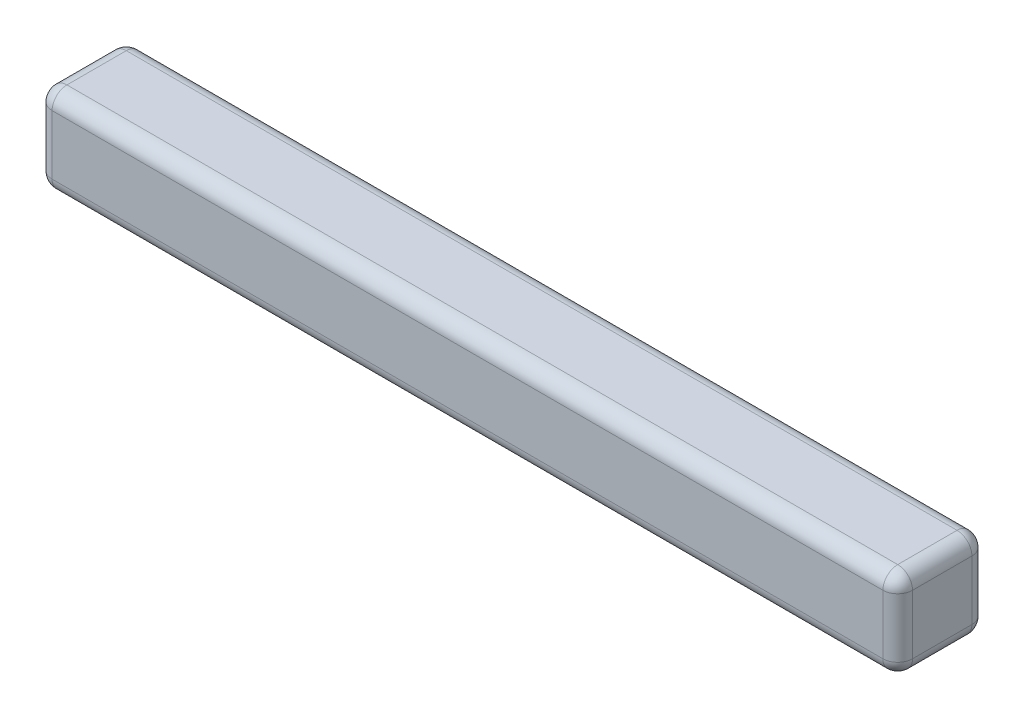
SolidWorks part; units mm, degrees
ref_plane "Front Plane" through (0, 0, 0) normal (0, 0, 1) x (1, 0, 0)
ref_plane "Top Plane" through (0, 0, 0) normal (0, 1, 0) x (1, 0, 0)
ref_plane "Right Plane" through (0, 0, 0) normal (1, 0, 0) x (0, 0, -1)
sketch "Sketch2" plane through (0, 0, 0) normal (1, 0, 0) x (0, 0, -1)
  line L0 (-37.2436, 144.124) -> (-40.3436, 144.124) construction
  line L5 (-40.2936, 141.074) -> (-37.2936, 141.074)
  line L6 (-40.2936, 141.074) -> (-40.2936, 144.074)
  line L7 (-40.2936, 144.074) -> (-37.2936, 144.074)
  line L8 (-37.2936, 141.074) -> (-37.2936, 144.074)
  line L9 (-37.2436, 141.024) -> (-40.3436, 141.024) construction
  line L10 (-37.2436, 144.124) -> (-37.2436, 141.024) construction
  line L11 (-40.3436, 144.124) -> (-40.3436, 141.024) construction
  dimension "D1" = 0.05
  dimension "D2" = 0.05
  dimension "D3" = 0.05
  dimension "D4" = 0.05
extrude "Boss-Extrude1" add sketch "Sketch2" along normal up to surface (29 mm away) from surface at 11.4401
fillet "Fillet1" radius 0.5 4 edges at (25.9401, 144.074, 37.2936) (25.9401, 144.074, 40.2936) (25.9401, 141.074, 37.2936) (25.9401, 141.074, 40.2936)
fillet "Fillet3" radius 0.5 16 edges at (40.4401, 141.2205, 37.44) (40.4401, 141.074, 38.7936) (40.4401, 141.2205, 40.1471) (40.4401, 142.574, 40.2936) (40.4401, 143.9276, 40.1471) (40.4401, 144.074, 38.7936) (40.4401, 143.9276, 37.44) (40.4401, 142.574, 37.2936) (11.4401, 143.9276, 40.1471) (11.4401, 142.574, 40.2936) (11.4401, 141.2205, 40.1471) (11.4401, 141.074, 38.7936) (11.4401, 141.2205, 37.44) (11.4401, 142.574, 37.2936) (11.4401, 143.9276, 37.44) (11.4401, 144.074, 38.7936)
